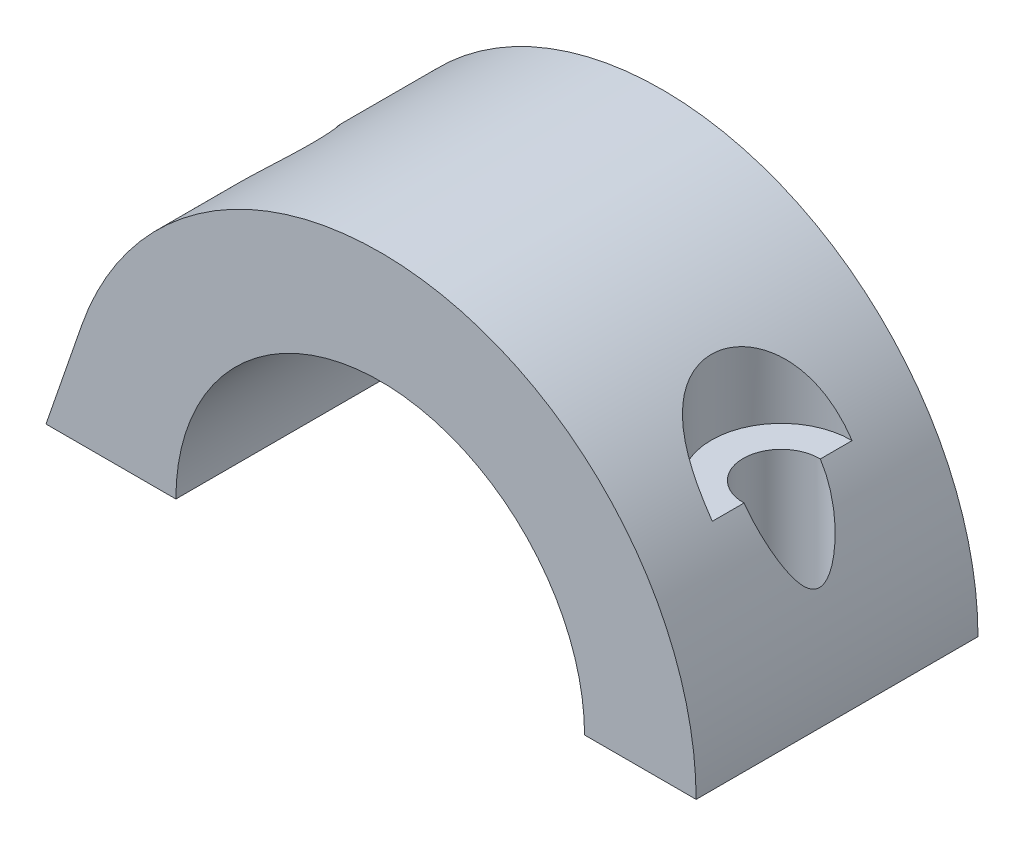
SolidWorks part; units mm, degrees
ref_plane "Front Plane" through (0, 0, 0) normal (0, 0, 1) x (1, 0, 0)
ref_plane "Top Plane" through (0, 0, 0) normal (0, 1, 0) x (1, 0, 0)
ref_plane "Right Plane" through (0, 0, 0) normal (1, 0, 0) x (0, 0, -1)
sketch "Sketch1" plane through (0, 0, 0) normal (0, 0, 1) x (1, 0, 0)
  line L0 (-8.04, 0) -> (-13.15, 0)
  line L2 (-13.15, 0) -> (-11.7494, 4.0566)
  line L9 (8.04, 0) -> (12.43, 0)
  arc A0 (0, 8.04) -> (-8.04, 0) centre (0, 0) ccw
  arc A2 (12.43, 0) -> (-11.7494, 4.0566) centre (0, 0) ccw
  arc A3 (0, 8.04) -> (8.04, 0) centre (0, 0) cw
  dimension "D1" = 5.11
  dimension "D3" = 8.04
  dimension "D2" = 4.39
extrude "Boss-Extrude1" add sketch "Sketch1" along normal blind 11.09
sketch "Sketch3" plane through (0, 0, 0) normal (0, -1, 0) x (1, 0, 0)
  line L0 (-13.15, 11.09) -> (-8.04, 11.09) construction
  line L1 (-10.595, 11.09) -> (-10.595, 5.95) construction
  line L5 (8.04, 11.09) -> (12.43, 11.09) construction
  line L6 (10.235, 11.09) -> (10.235, 5.545) construction
  circle A0 centre (-10.595, 5.95) radius 1.5
  circle A2 centre (10.235, 5.545) radius 1.5
  dimension "D1" = 3
ref_plane "Plane1" through (0, 9.5, 0) normal (0, 1, 0) x (1, 0, 0)
extrude "Cut-Extrude4" cut sketch "Sketch3" against normal blind 10
sketch "Sketch4" plane through (0, 9.5, 0) normal (0, 1, 0) x (1, 0, 0)
  circle A2 centre (-10.595, -5.95) radius 2.75
  circle A3 centre (10.235, -5.545) radius 2.75
extrude "Cut-Extrude3" cut sketch "Sketch4" against normal mid plane 5
